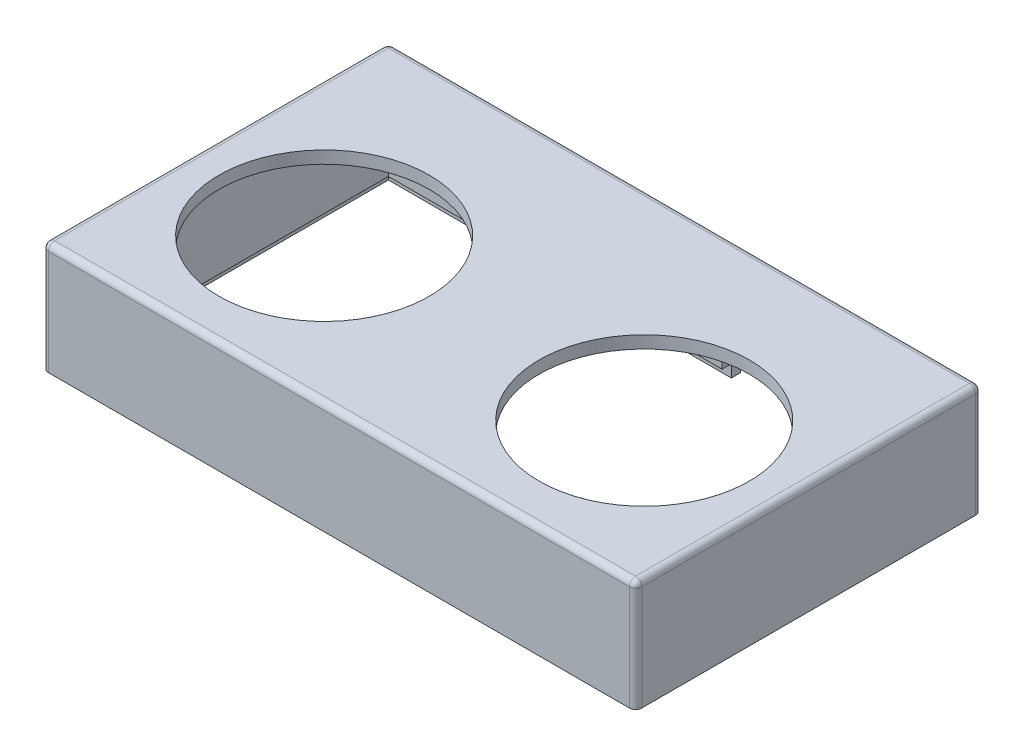
SolidWorks part; units mm, degrees
ref_plane "Front Plane" through (0, 0, 0) normal (0, 0, 1) x (1, 0, 0)
ref_plane "Top Plane" through (0, 0, 0) normal (0, 1, 0) x (1, 0, 0)
ref_plane "Right Plane" through (0, 0, 0) normal (1, 0, 0) x (0, 0, -1)
sketch "Sketch1" plane through (0, 0, 0) normal (0, 1, 0) x (1, 0, 0)
  line L1 (-24, -14) -> (24, -14)
  line L2 (-24, -14) -> (-24, 14)
  line L3 (-24, 14) -> (24, 14)
  line L4 (24, -14) -> (24, 14)
  line L5 (-24, -14) -> (24, 14) construction
  line L6 (-24, 14) -> (24, -14) construction
  point P0 (0, 0)
  dimension "D1" = 28
  dimension "D2" = 48
extrude "Boss-Extrude1" add sketch "Sketch1" along normal blind 9
sketch "Sketch2" plane through (0, 0, 0) normal (0, -1, 0) x (1, 0, 0)
  line L1 (-22.5, -12.5) -> (22.5, -12.5)
  line L2 (-22.5, -12.5) -> (-22.5, 12.5)
  line L3 (-22.5, 12.5) -> (22.5, 12.5)
  line L4 (22.5, -12.5) -> (22.5, 12.5)
  line L5 (-22.5, -12.5) -> (22.5, 12.5) construction
  line L6 (-22.5, 12.5) -> (22.5, -12.5) construction
  point P0 (0, 0)
  dimension "D1" = 45
  dimension "D2" = 25
extrude "Cut-Extrude1" cut sketch "Sketch2" against normal blind 8
sketch "Sketch3" plane through (0, 9, 0) normal (0, 1, 0) x (1, 0, 0)
  line L0 (-24, -14) -> (24, -14) construction
  line L1 (24, -14) -> (24, 14) construction
  circle A0 centre (-12.95, -2.25) radius 8.5
  circle A1 centre (12.95, -2.25) radius 8.5
  dimension "D1" = 17
  dimension "D2" = 17
  dimension "D3" = 25.9
  dimension "D4" = 11.75
  dimension "D5" = 11.05
  dimension "D6" = 11.75
extrude "Cut-Extrude2" cut sketch "Sketch3" against normal blind 22
sketch "Sketch4" plane through (0, 0, 0) normal (0, -1, 0) x (1, 0, 0)
  line L1 (-23.25, -13.25) -> (23.25, -13.25)
  line L2 (-23.25, -13.25) -> (-23.25, 13.25)
  line L3 (-23.25, 13.25) -> (23.25, 13.25)
  line L4 (23.25, -13.25) -> (23.25, 13.25)
  line L5 (-23.25, -13.25) -> (23.25, 13.25) construction
  line L6 (-23.25, 13.25) -> (23.25, -13.25) construction
  point P0 (0, 0)
  dimension "D1" = 46.5
  dimension "D2" = 26.5
extrude "Cut-Extrude3" cut sketch "Sketch4" against normal blind 1
sketch "Sketch10" plane through (0, 0, 0) normal (0, 0, 1) x (1, 0, 0)
  line L1 (12.5, 0) -> (4.5, 0)
  line L2 (12.5, 0) -> (12.5, 3.5)
  line L3 (12.5, 3.5) -> (4.5, 3.5)
  line L4 (4.5, 0) -> (4.5, 3.5)
  line L5 (12.5, 0) -> (4.5, 3.5) construction
  line L6 (12.5, 3.5) -> (4.5, 0) construction
  line L7 (22.5, 8) -> (22.5, 1) construction
  point P0 (8.5, 1.75)
  dimension "D1" = 8
  dimension "D2" = 3.5
  dimension "D3" = 1.75
  dimension "D4" = 10
extrude "Cut-Extrude4" cut sketch "Sketch10" against normal through all
fillet "Fillet5" radius 0.5 8 edges at (0, 9, -14) (24, 4.5, -14) (24, 4.5, 14) (-24, 4.5, -14) (-24, 9, 0) (-24, 4.5, 14) (0, 9, 14) (24, 9, 0)
